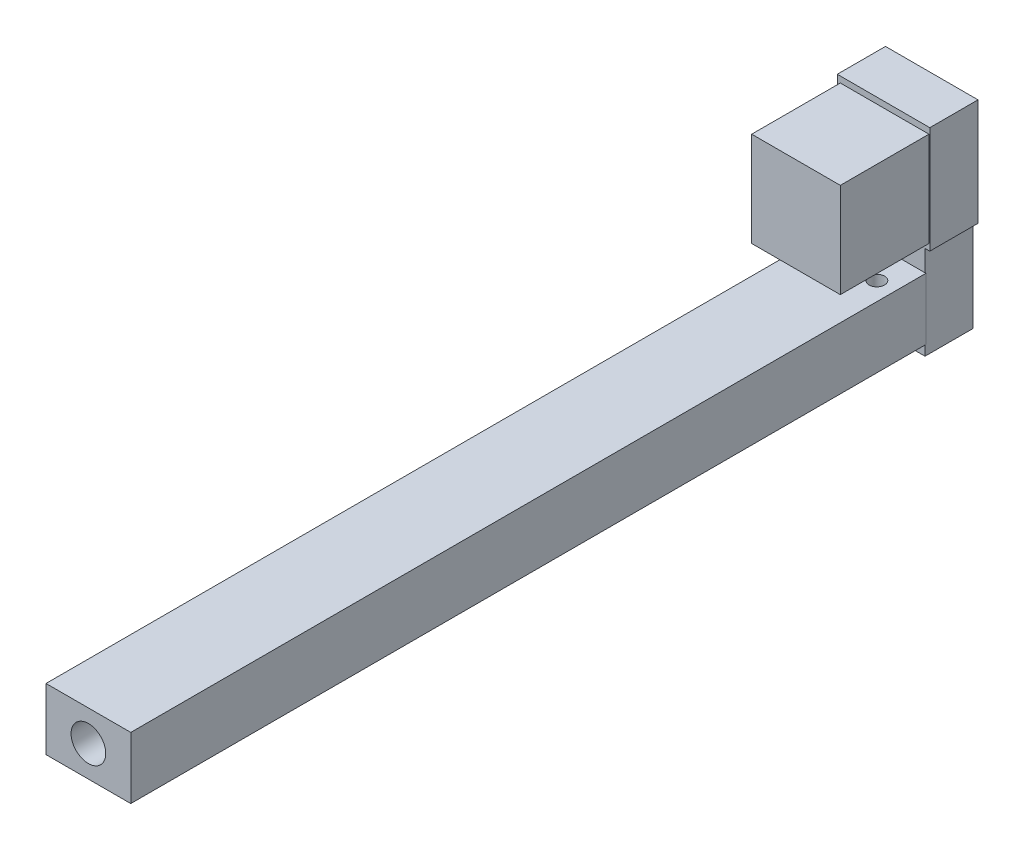
SolidWorks part; units mm, degrees
ref_plane "Front Plane" through (0, 0, 0) normal (0, 0, 1) x (1, 0, 0)
ref_plane "Top Plane" through (0, 0, 0) normal (0, 1, 0) x (1, 0, 0)
ref_plane "Right Plane" through (0, 0, 0) normal (1, 0, 0) x (0, 0, -1)
sketch "Sketch1" plane through (0, 0, 0) normal (1, 0, 0) x (0, 0, -1)
  line L1 (0, 50.8) -> (-1310.386, 50.8)
  line L2 (0, 50.8) -> (0, -50.8)
  line L3 (0, -50.8) -> (-1310.386, -50.8)
  line L4 (-1310.386, 50.8) -> (-1310.386, -50.8)
  point P4 (0, 0)
  dimension "D1" = 1310.386
  dimension "D2" = 101.6
  dimension "D3" = 0
extrude "Boss-Extrude1" add sketch "Sketch1" along normal mid plane 139.7
sketch "Sketch2" plane through (0, 0, 0) normal (1, 0, 0) x (0, 0, -1)
  line L0 (0, 0) -> (0, -68.326)
  line L1 (0, -68.326) -> (79.4308, -68.326)
  line L2 (79.4308, -68.326) -> (79.4308, 85.598)
  line L3 (79.4308, 85.598) -> (0, 85.598)
  line L4 (0, 85.598) -> (0, 0)
  dimension "D1" = 68.326
  dimension "D2" = 153.924
extrude "Boss-Extrude2" add sketch "Sketch2" along normal mid plane 136.652 contours L3 L4 L0 L1 L2
sketch "Sketch3" plane through (0, 0, 0) normal (1, 0, 0) x (0, 0, -1)
  line L1 (0, 85.598) -> (79.4308, 85.598)
  line L2 (0, 85.598) -> (0, 261.868)
  line L3 (0, 261.868) -> (79.4308, 261.868)
  line L4 (79.4308, 85.598) -> (79.4308, 261.868)
  dimension "D1" = 176.27
extrude "Boss-Extrude3" add sketch "Sketch3" along normal mid plane 152.46
sketch "Sketch4" plane through (0, 0, 0) normal (0, 0, 1) x (1, 0, 0)
  line L0 (-76.23, 261.868) -> (-76.23, 85.598) construction
  line L1 (-71.23, 251.868) -> (74.81, 251.868)
  line L2 (-71.23, 251.868) -> (-71.23, 95.828)
  line L3 (-71.23, 95.828) -> (74.81, 95.828)
  line L4 (74.81, 251.868) -> (74.81, 95.828)
  line L6 (76.23, 261.868) -> (-76.23, 261.868) construction
  dimension "D1" = 156.04
  dimension "D2" = 146.04
  dimension "D3" = 5
  dimension "D4" = 10
extrude "Boss-Extrude4" add sketch "Sketch4" along normal blind 146.05
sketch "Sketch5" plane through (0, 0, 1310.386) normal (0, 0, 1) x (1, 0, 0)
  circle A0 centre (0, 0) radius 28.575
  dimension "D1" = 57.15
extrude "Cut-Extrude1" cut sketch "Sketch5" against normal blind 927.1
sketch "Sketch6" plane through (0, 50.8, 0) normal (0, 1, 0) x (1, 0, 0)
  line L0 (76.23, 0) -> (-76.23, 0) construction
  line L1 (74.81, -146.05) -> (74.81, 0) construction
  circle A0 centre (39.81, -50.8) radius 12.7
  dimension "D1" = 25.4
  dimension "D2" = 50.8
  dimension "D3" = 35
extrude "Cut-Extrude2" cut sketch "Sketch6" along normal blind 10 and the other way through all
